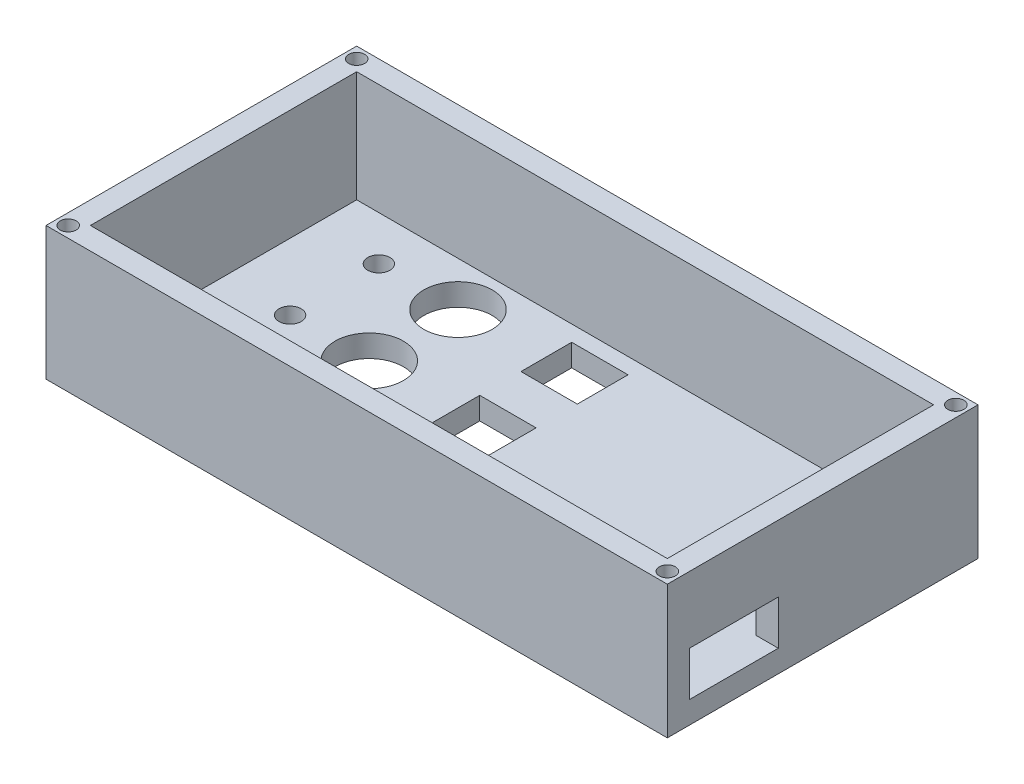
SolidWorks part; units mm, degrees
material "PC High Viscosity"
ref_plane "Front Plane" through (0, 0, 0) normal (0, 0, 1) x (1, 0, 0)
ref_plane "Top Plane" through (0, 0, 0) normal (0, 1, 0) x (1, 0, 0)
ref_plane "Right Plane" through (0, 0, 0) normal (1, 0, 0) x (0, 0, -1)
sketch "Sketch1" plane through (0, 0, 0) normal (0, 1, 0) x (1, 0, 0)
  line L1 (0, 0) -> (140, 0)
  line L2 (0, 0) -> (0, 70)
  line L3 (0, 70) -> (140, 70)
  line L4 (140, 0) -> (140, 70)
extrude "Boss-Extrude1" add sketch "Sketch1" along normal blind 30 contours L2 L1 L4 L3
sketch "Sketch2" plane through (0, 30, 0) normal (0, 1, 0) x (1, 0, 0)
  line L0 (0, 0) -> (5, 0)
  line L1 (0, 0) -> (140, 0) construction
  line L2 (5, 0) -> (5, 5)
  line L4 (5, 5) -> (135, 5)
  line L5 (5, 5) -> (5, 65)
  line L6 (5, 65) -> (135, 65)
  line L7 (135, 5) -> (135, 65)
  line L8 (5, 5) -> (135, 5)
  line L9 (5, 5) -> (5, 65)
  line L10 (5, 65) -> (135, 65)
  line L11 (135, 5) -> (135, 65)
  line L12 (5, 5) -> (135, 5)
  line L13 (5, 5) -> (5, 65)
  line L14 (5, 65) -> (135, 65)
  line L15 (135, 5) -> (135, 65)
extrude "Cut-Extrude1" cut sketch "Sketch2" against normal blind 25 contours L4 L7 L6 L5
sketch "Sketch3" plane through (0, 0, 0) normal (0, -1, 0) x (1, 0, 0)
  line L0 (0, 0) -> (20, 0)
  line L1 (0, 0) -> (140, 0) construction
  line L2 (20, 0) -> (20, -70)
  line L3 (0, -70) -> (140, -70) construction
  line L4 (20, -35) -> (20, -15)
  line L5 (20, -35) -> (55.6676, -35)
  line L6 (37.8338, -35) -> (37.8338, -15)
  line L7 (55.6676, -35) -> (68.3676, -35)
  line L11 (55.6676, -35) -> (68.3676, -35)
  line L15 (37.8338, -35) -> (37.8338, -55)
  line L16 (62.0176, -35) -> (62.0176, -20)
  line L17 (62.0176, -35) -> (62.0176, -50)
  line L19 (57.0176, -15) -> (57.0176, -8.57)
  line L20 (57.0176, -8.57) -> (69.7176, -8.57)
  line L21 (69.7176, -8.57) -> (69.7176, -20)
  line L22 (69.7176, -20) -> (57.0176, -20)
  line L23 (57.0176, -20) -> (57.0176, -15)
  line L24 (69.7176, -61.43) -> (69.7176, -50)
  line L28 (69.7176, -50) -> (57.0176, -50)
  line L31 (57.0176, -40.715) -> (68.3676, -40.715)
  line L33 (68.3676, -29.285) -> (57.0176, -29.285)
  line L35 (68.3676, -29.285) -> (69.7176, -29.285)
  line L36 (69.7176, -29.285) -> (69.7176, -40.715)
  line L37 (69.7176, -40.715) -> (57.0176, -40.715)
  line L38 (57.0176, -40.715) -> (57.0176, -29.285)
  line L39 (57.0176, -29.285) -> (69.7176, -29.285)
  line L40 (57.0176, -40.715) -> (69.7176, -40.715)
  line L41 (57.0176, -40.715) -> (57.0176, -29.285)
  line L42 (57.0176, -29.285) -> (69.7176, -29.285)
  line L43 (69.7176, -40.715) -> (69.7176, -29.285)
  line L46 (57.0176, -50) -> (69.7176, -50)
  line L47 (69.7176, -61.43) -> (69.7176, -50)
  line L48 (57.0176, -50) -> (69.7176, -50)
  line L49 (57.0176, -50) -> (57.0176, -61.43)
  line L50 (57.0176, -61.43) -> (69.7176, -61.43)
  line L51 (69.7176, -50) -> (69.7176, -61.43)
  circle A0 centre (20, -35) radius 2.5
  circle A1 centre (20, -15) radius 2.5
  circle A2 centre (20, -55) radius 2.5
  circle A3 centre (37.8338, -35) radius 7.7
  circle A4 centre (37.8338, -55) radius 7.7
  circle A5 centre (37.8338, -15) radius 7.7
extrude "Cut-Extrude2" cut sketch "Sketch3" against normal blind 25 contours A2 L2 | A2 L2 | L2 A0 L5 | L4 A0 L2 | L5 A0 L4 | L2 A1 | L2 A1
sketch "Sketch4" plane through (140, 0, 0) normal (1, 0, 0) x (0, 0, -1)
  line L0 (0, 0) -> (0, 5)
  line L1 (0, 30) -> (0, 0) construction
  line L2 (0, 5) -> (5, 5)
  line L4 (5, 5) -> (25, 5)
  line L5 (5, 5) -> (5, 15)
  line L6 (5, 15) -> (25, 15)
  line L7 (25, 5) -> (25, 15)
extrude "Cut-Extrude6" cut sketch "Sketch4" against normal blind 25 contours L4 L7 L6 L5
sketch "Sketch5" plane through (0, 30, 0) normal (0, 1, 0) x (1, 0, 0)
  line L0 (0, 0) -> (5, 5)
  line L2 (2.5, 2.5) -> (137.5, 2.5)
  line L3 (2.5, 2.5) -> (2.5, 67.5)
  line L4 (2.5, 67.5) -> (137.5, 67.5)
  line L5 (137.5, 2.5) -> (137.5, 67.5)
hole_wizard "M3 Clearance Hole1" positions "Sketch6" profile "Sketch8" hole size "M3" standard "ANSI Metric"
sketch "Sketch6" plane through (0, 30, 0) normal (0, 1, 0) x (1, 0, 0)
  point P0 (2.5, 2.5)
  point P3 (2.5, 67.5)
  point P6 (137.5, 67.5)
  point P9 (137.5, 2.5)
sketch "Sketch8" plane through (2.5, 30, -2.5) normal (1, 0, 0) x (0, 0, 1)
  line L0 (0, 0) -> (0, 6.0815)
  line L1 (0, 6.0815) -> (1.8, 5)
  line L2 (1.8, 5) -> (1.8, 0)
  line L5 (1.8, 0) -> (0, 0)
  line L10 (0, 6.0815) -> (-1.8, 5) construction
  line L11 (0, -6.35) -> (0, 107.95) construction
  dimension "Hole Dia." = 3.6
  dimension "Hole Depth" = 5
  dimension "Drill Angle" = 118
